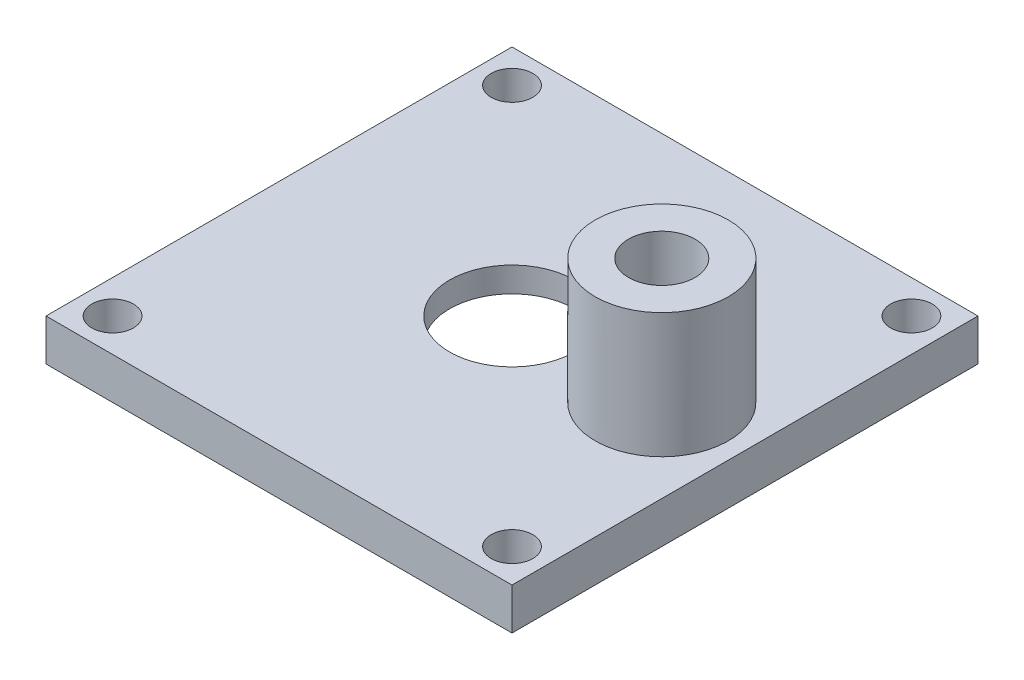
SolidWorks part; units mm, degrees
ref_plane "Front Plane" through (0, 0, 0) normal (0, 0, 1) x (1, 0, 0)
ref_plane "Top Plane" through (0, 0, 0) normal (0, 1, 0) x (1, 0, 0)
ref_plane "Right Plane" through (0, 0, 0) normal (1, 0, 0) x (0, 0, -1)
sketch "Sketch1" plane through (0, 0, 0) normal (0, 1, 0) x (1, 0, 0)
  line L1 (-28, -28) -> (28, -28)
  line L2 (-28, -28) -> (-28, 28)
  line L3 (-28, 28) -> (28, 28)
  line L4 (28, -28) -> (28, 28)
  line L5 (-28, -28) -> (28, 28) construction
  line L6 (-28, 28) -> (28, -28) construction
  point P0 (0, 0)
  dimension "D1" = 56
  dimension "D2" = 56
extrude "Boss-Extrude1" add sketch "Sketch1" along normal blind 5
sketch "Sketch2" plane through (0, 5, 0) normal (0, 1, 0) x (1, 0, 0)
  circle A0 centre (18, 0) radius 8
  point P2 (0, 0)
  dimension "D1" = 16
  dimension "D2" = 0
  dimension "D3" = 18
extrude "Boss-Extrude2" add sketch "Sketch2" along normal blind 15
sketch "Sketch4" plane through (0, 0, 0) normal (0, -1, 0) x (1, 0, 0)
  circle A0 centre (0, 0) radius 19
  dimension "D1" = 38
extrude "Cut-Extrude2" cut sketch "Sketch4" against normal blind 2
sketch "Sketch5" plane through (0, 2, 0) normal (0, -1, 0) x (1, 0, 0)
  circle A0 centre (0, 0) radius 7.5
  dimension "D1" = 15
extrude "Cut-Extrude3" cut sketch "Sketch5" against normal through all and the other way through all
sketch "Sketch6" plane through (0, 20, 0) normal (0, 1, 0) x (1, 0, 0)
  circle A0 centre (18, 0) radius 4
  dimension "D1" = 8
extrude "Cut-Extrude4" cut sketch "Sketch6" along direction (0, -1, 0) on the side against the normal up to surface (15 mm away)
sketch "Sketch7" plane through (0, 5, 0) normal (0, 1, 0) x (1, 0, 0)
  circle A0 centre (-24, 24) radius 2.5
  circle A1 centre (24, 24) radius 2.5
  circle A2 centre (24, -24) radius 2.5
  circle A3 centre (-24, -24) radius 2.5
  point P2 (0, 0)
  point P13 (0, 0)
  dimension "D1" = 24
  dimension "D2" = 5
  dimension "D3" = 24
  dimension "D4" = 4
extrude "Cut-Extrude5" cut sketch "Sketch7" against normal through all
